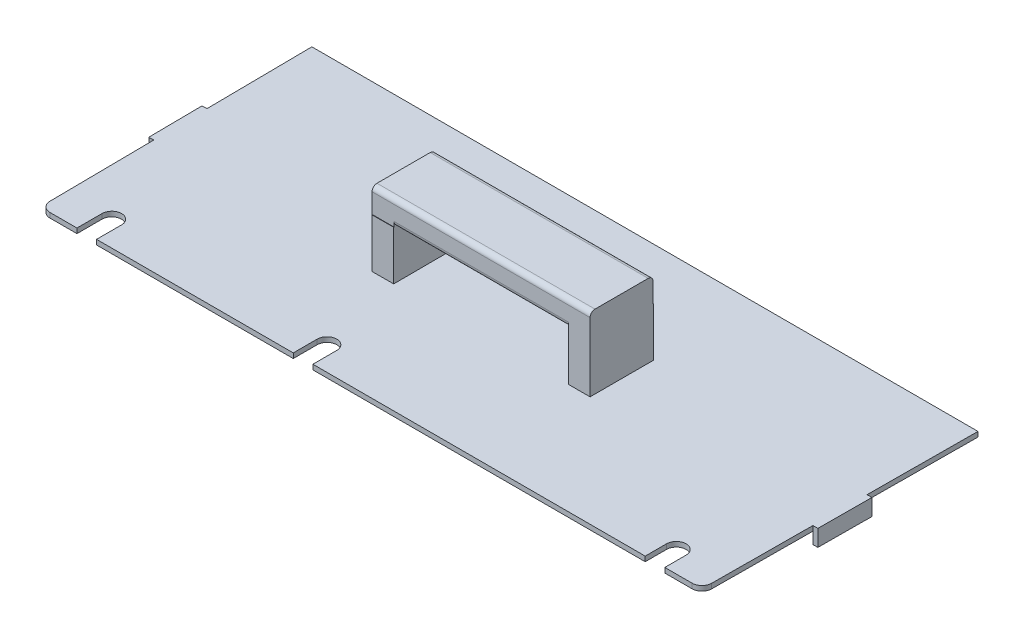
SolidWorks part; units mm, degrees
ref_plane "Front Plane" through (0, 0, 0) normal (0, 0, 1) x (1, 0, 0)
ref_plane "Top Plane" through (0, 0, 0) normal (0, 1, 0) x (1, 0, 0)
ref_plane "Right Plane" through (0, 0, 0) normal (1, 0, 0) x (0, 0, -1)
sketch "Sketch1" plane through (0, 0, 0) normal (0, 1, 0) x (1, 0, 0)
  line L0 (76.5987, -62.781) -> (76.9407, -8.3109) construction
  line L5 (-56.3502, -64.7684) -> (74.5987, -64.7684) construction
  line L6 (-58.9164, -8.3109) -> (-58.3501, -62.7892) construction
  line L7 (76.5987, -62.781) -> (76.9376, -8.8109)
  line L8 (-56.3502, -64.7684) -> (74.5987, -64.7684)
  line L9 (-58.9112, -8.8109) -> (-58.3501, -62.7892)
  line L10 (-58.9112, -8.8109) -> (76.9376, -8.8109)
  line L11 (75.9344, -9.3109) -> (-57.9059, -9.3109) construction
  arc A0 (74.5987, -64.7684) -> (76.5987, -62.781) centre (74.5987, -62.7684) ccw construction
  arc A1 (-58.3501, -62.7892) -> (-56.3502, -64.7684) centre (-56.3502, -62.7684) ccw construction
  arc A2 (74.5987, -64.7684) -> (76.5987, -62.781) centre (74.5987, -62.7684) ccw
  arc A3 (-58.3501, -62.7892) -> (-56.3502, -64.7684) centre (-56.3502, -62.7684) ccw
  dimension "D1" = 0.5
extrude "Boss-Extrude1" add sketch "Sketch1" along normal blind 1
sketch "Sketch3" plane through (0, 1, 0) normal (0, 1, 0) x (1, 0, 0)
  line L0 (-58.6307, -35.8) -> (76.7682, -35.7959) construction
  line L1 (-58.9112, -8.8109) -> (-58.3501, -62.7892) construction
  line L2 (76.5987, -62.781) -> (76.9376, -8.8109) construction
  line L3 (9.0132, -8.8109) -> (9.1243, -64.7684) construction
  line L4 (76.9376, -8.8109) -> (-58.9112, -8.8109) construction
  line L5 (-56.3502, -64.7684) -> (74.5987, -64.7684) construction
  line L6 (-13.1214, -42.3565) -> (-8.6886, -42.3389)
  line L7 (31.2808, -42.2684) -> (26.8479, -42.2684)
  line L8 (31.2808, -42.2684) -> (31.2808, -29.3264)
  line L9 (31.2808, -29.3264) -> (26.8479, -29.3264)
  line L10 (26.8479, -42.2684) -> (26.8479, -29.3264)
  line L11 (31.2808, -42.2684) -> (26.8479, -29.3264) construction
  line L12 (31.2808, -29.3264) -> (26.8479, -42.2684) construction
  line L13 (-8.6886, -42.3389) -> (-8.74, -29.397)
  line L14 (-13.1728, -29.4146) -> (-8.74, -29.397)
  line L15 (-13.1214, -42.3565) -> (-13.1728, -29.4146)
  point P12 (29.0644, -35.7974)
extrude "Boss-Extrude4" add sketch "Sketch3" along normal blind 10
sketch "Sketch4" plane through (0, 11, 0) normal (0, 1, 0) x (1, 0, 0)
  line L1 (-13.1728, -29.4146) -> (31.2808, -29.4146)
  line L2 (-13.1728, -29.4146) -> (-13.1728, -42.2684)
  line L3 (-13.1728, -42.2684) -> (31.2808, -42.2684)
  line L4 (31.2808, -29.4146) -> (31.2808, -42.2684)
extrude "Boss-Extrude6" add sketch "Sketch4" along normal blind 5 contours L2 L3 L4 L1
sketch "Sketch5" plane through (0, 1, 0) normal (0, 1, 0) x (1, 0, 0)
  line L0 (-50.8652, -59.6581) -> (-50.8652, -64.7684)
  line L1 (-56.3502, -64.7684) -> (74.5987, -64.7684) construction
  line L2 (-50.8652, -64.7684) -> (-46.8652, -64.7684)
  line L3 (-46.8652, -64.7684) -> (-46.8652, -59.6581)
  line L4 (-6.7485, -59.8904) -> (-6.7485, -64.7684)
  line L5 (-6.7485, -64.7684) -> (-2.7485, -64.7684)
  line L6 (-2.7485, -64.7684) -> (-2.7485, -59.8904)
  line L7 (65.0243, -60.427) -> (65.0243, -64.7684)
  line L8 (65.0243, -64.7684) -> (69.0243, -64.7684)
  line L9 (69.0243, -64.7684) -> (69.0243, -60.427)
  circle A0 centre (67.0243, -60.427) radius 2 construction
  circle A1 centre (-4.7485, -59.8904) radius 2 construction
  circle A2 centre (-48.8652, -59.6581) radius 2 construction
  arc A3 (69.0243, -60.427) -> (65.0243, -60.427) centre (67.0243, -60.427) ccw
  arc A4 (-2.7485, -59.8904) -> (-6.7485, -59.8904) centre (-4.7485, -59.8904) ccw
  arc A5 (-46.8652, -59.6581) -> (-50.8652, -59.6581) centre (-48.8652, -59.6581) ccw
extrude "Cut-Extrude1" cut sketch "Sketch5" against normal blind 5
fillet "Fillet3" radius 1 2 edges at (9.054, 16, 29.4146) (9.054, 16, 42.2684)
fillet "Fillet4" radius 1 2 edges at (9.054, 11, 29.4146) (9.0795, 11, 42.2684)
sketch "Sketch7" plane through (-58.9964, 0, 0.6132) normal (-0.9999, 0, 0.0104) x (0.0104, 0, 0.9999)
  line L0 (8.1981, 1) -> (62.1793, 1) construction
  line L1 (29.8163, 1) -> (40.785, 1)
  line L2 (29.8163, 1) -> (29.8163, -2.3704)
  line L3 (29.8163, -2.3704) -> (40.785, -2.3704)
  line L4 (40.785, 1) -> (40.785, -2.3704)
extrude "Boss-Extrude7" add sketch "Sketch7" along normal blind 1
sketch "Sketch9" plane through (76.9899, 0, 0.4835) normal (1, 0, 0.0063) x (0.0063, 0, -1)
  line L4 (-30.8126, -2.3704) -> (-30.8126, 1)
  line L5 (-41.7797, -2.3704) -> (-30.8126, -2.3704)
  line L6 (-41.7797, 1) -> (-41.7797, -2.3704)
  line L7 (-30.8126, 1) -> (-41.7797, 1)
  line L8 (-30.8126, -2.3704) -> (-30.8126, 1)
  line L9 (-41.7797, -2.3704) -> (-30.8126, -2.3704)
  line L10 (-41.7797, 1) -> (-41.7797, -2.3704)
  line L11 (-30.8126, 1) -> (-41.7797, 1)
  dimension "D1" = 0
extrude "Boss-Extrude8" add sketch "Sketch9" along normal blind 1
